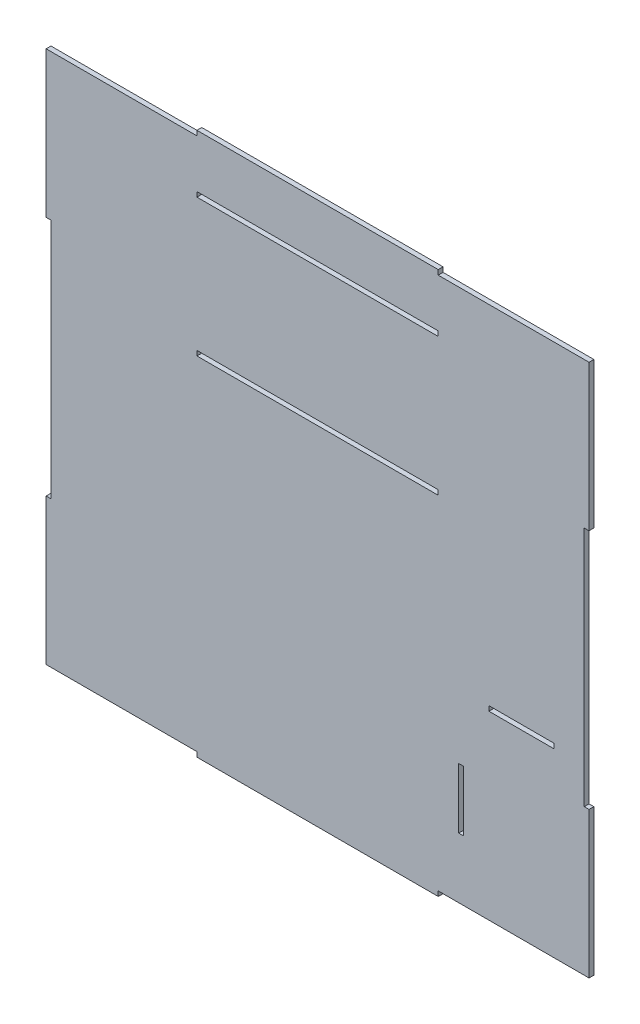
SolidWorks part; units mm, degrees
ref_plane "Front Plane" through (0, 0, 0) normal (0, 0, 1) x (1, 0, 0)
ref_plane "Top Plane" through (0, 0, 0) normal (0, 1, 0) x (1, 0, 0)
ref_plane "Right Plane" through (0, 0, 0) normal (1, 0, 0) x (0, 0, -1)
sketch "Sketch1" plane through (0, 0, 0) normal (0, 0, 1) x (1, 0, 0)
  line L0 (-253.6803, -226.8994) -> (-128.6803, -226.8994)
  line L1 (-128.6803, -226.8994) -> (-128.6803, -230.8994)
  line L2 (-128.6803, -230.8994) -> (71.3197, -230.8994)
  line L3 (71.3197, -230.8994) -> (71.3197, -226.8994)
  line L4 (71.3197, -226.8994) -> (196.3197, -226.8994)
  line L5 (196.3197, -226.8994) -> (196.3197, -105.8994)
  line L6 (196.3197, -105.8994) -> (192.3197, -105.8994)
  line L7 (192.3197, -105.8994) -> (192.3197, 94.1006)
  line L8 (192.3197, 94.1006) -> (196.3197, 94.1006)
  line L9 (196.3197, 94.1006) -> (196.3197, 215.1006)
  line L10 (196.3197, 215.1006) -> (71.3197, 215.1006)
  line L11 (71.3197, 215.1006) -> (71.3197, 219.1006)
  line L12 (71.3197, 219.1006) -> (-128.6803, 219.1006)
  line L13 (-128.6803, 219.1006) -> (-128.6803, 215.1006)
  line L14 (-128.6803, 215.1006) -> (-253.6803, 215.1006)
  line L15 (-253.6803, 215.1006) -> (-253.6803, 94.1006)
  line L16 (-253.6803, 94.1006) -> (-249.6803, 94.1006)
  line L17 (-249.6803, 94.1006) -> (-249.6803, -105.8994)
  line L18 (-249.6803, -105.8994) -> (-253.6803, -105.8994)
  line L19 (-253.6803, -105.8994) -> (-253.6803, -226.8994)
  line L21 (92.3197, -126.8994) -> (88.3197, -126.8994)
  line L22 (92.3197, -126.8994) -> (92.3197, -176.8994)
  line L23 (92.3197, -176.8994) -> (88.3197, -176.8994)
  line L24 (88.3197, -126.8994) -> (88.3197, -176.8994)
  line L25 (113.3197, -72.8994) -> (167.3197, -72.8994)
  line L26 (113.3197, -72.8994) -> (113.3197, -76.8994)
  line L27 (113.3197, -76.8994) -> (167.3197, -76.8994)
  line L28 (167.3197, -72.8994) -> (167.3197, -76.8994)
  line L29 (-128.6803, 61.1006) -> (71.3197, 61.1006)
  line L30 (-128.6803, 61.1006) -> (-128.6803, 57.1006)
  line L31 (-128.6803, 57.1006) -> (71.3197, 57.1006)
  line L32 (71.3197, 61.1006) -> (71.3197, 57.1006)
  line L33 (-128.6803, 175.1006) -> (71.3197, 175.1006)
  line L34 (-128.6803, 175.1006) -> (-128.6803, 171.1006)
  line L35 (-128.6803, 171.1006) -> (71.3197, 171.1006)
  line L36 (71.3197, 175.1006) -> (71.3197, 171.1006)
  dimension "D1" = 4
  dimension "D2" = 110
  dimension "D3" = 200
extrude "Boss-Extrude1" add sketch "Sketch1" along normal blind 4
sketch "Sketch2" plane through (0, 0, 4) normal (0, 0, 1) x (1, 0, 0)
  line L20 (-253.6803, -105.8994) -> (-253.6803, -226.8994)
  line L21 (-253.6803, -226.8994) -> (-128.6803, -226.8994)
  line L22 (-128.6803, -226.8994) -> (-128.6803, -230.8994)
  line L23 (-128.6803, -230.8994) -> (71.3197, -230.8994)
  line L24 (71.3197, -230.8994) -> (71.3197, -226.8994)
  line L25 (71.3197, -226.8994) -> (196.3197, -226.8994)
  line L26 (196.3197, -226.8994) -> (196.3197, -105.8994)
  line L27 (196.3197, -105.8994) -> (192.3197, -105.8994)
  line L28 (192.3197, -105.8994) -> (192.3197, 94.1006)
  line L29 (192.3197, 94.1006) -> (196.3197, 94.1006)
  line L30 (196.3197, 94.1006) -> (196.3197, 215.1006)
  line L31 (196.3197, 215.1006) -> (71.3197, 215.1006)
  line L32 (71.3197, 215.1006) -> (71.3197, 219.1006)
  line L33 (71.3197, 219.1006) -> (-128.6803, 219.1006)
  line L34 (-128.6803, 219.1006) -> (-128.6803, 215.1006)
  line L35 (-128.6803, 215.1006) -> (-253.6803, 215.1006)
  line L36 (-253.6803, 215.1006) -> (-253.6803, 94.1006)
  line L37 (-253.6803, 94.1006) -> (-249.6803, 94.1006)
  line L38 (-249.6803, 94.1006) -> (-249.6803, -105.8994)
  line L39 (-249.6803, -105.8994) -> (-253.6803, -105.8994)
  line L40 (-253.6803, -105.8994) -> (-253.6803, -226.8994)
  line L41 (-253.6803, -226.8994) -> (-128.6803, -226.8994)
  line L42 (-128.6803, -226.8994) -> (-128.6803, -230.8994)
  line L43 (-128.6803, -230.8994) -> (71.3197, -230.8994)
  line L44 (71.3197, -230.8994) -> (71.3197, -226.8994)
  line L45 (71.3197, -226.8994) -> (196.3197, -226.8994)
  line L46 (196.3197, -226.8994) -> (196.3197, -105.8994)
  line L47 (196.3197, -105.8994) -> (192.3197, -105.8994)
  line L48 (192.3197, -105.8994) -> (192.3197, 94.1006)
  line L49 (192.3197, 94.1006) -> (196.3197, 94.1006)
  line L50 (196.3197, 94.1006) -> (196.3197, 215.1006)
  line L51 (196.3197, 215.1006) -> (71.3197, 215.1006)
  line L52 (71.3197, 215.1006) -> (71.3197, 219.1006)
  line L53 (71.3197, 219.1006) -> (-128.6803, 219.1006)
  line L54 (-128.6803, 219.1006) -> (-128.6803, 215.1006)
  line L55 (-128.6803, 215.1006) -> (-253.6803, 215.1006)
  line L56 (-253.6803, 215.1006) -> (-253.6803, 94.1006)
  line L57 (-253.6803, 94.1006) -> (-249.6803, 94.1006)
  line L58 (-249.6803, 94.1006) -> (-249.6803, -105.8994)
  line L59 (-249.6803, -105.8994) -> (-253.6803, -105.8994)
  dimension "D1" = 0
